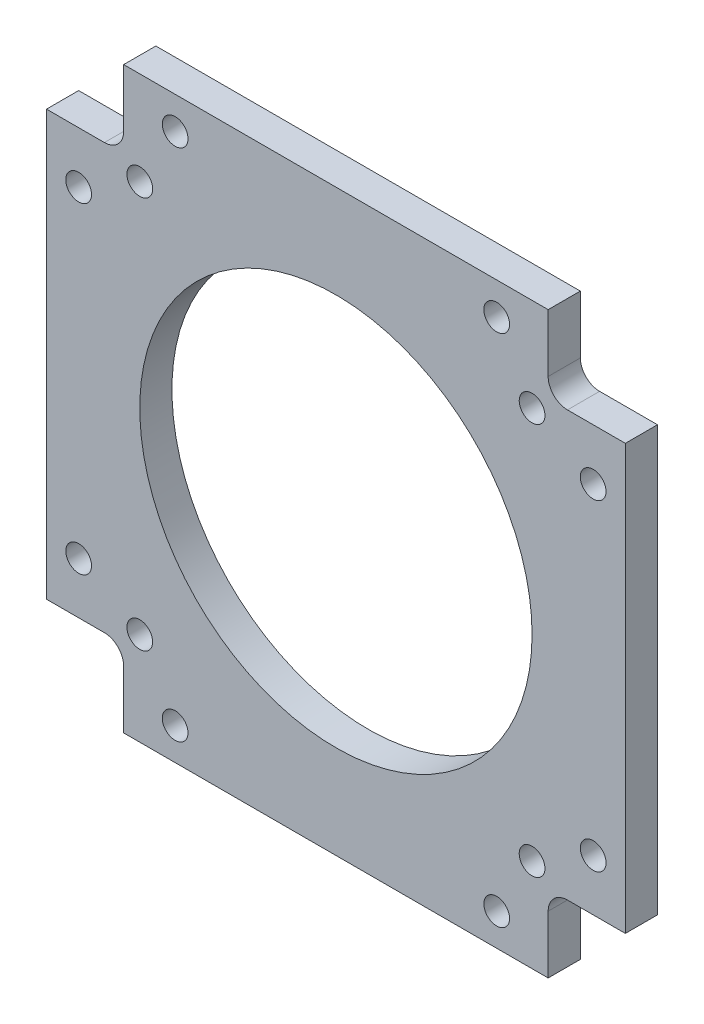
SolidWorks part; units mm, degrees
ref_plane "Front Plane" through (0, 0, 0) normal (0, 0, 1) x (1, 0, 0)
ref_plane "Top Plane" through (0, 0, 0) normal (0, 1, 0) x (1, 0, 0)
ref_plane "Right Plane" through (0, 0, 0) normal (1, 0, 0) x (0, 0, -1)
sketch "Sketch1" plane through (0, 0, 0) normal (0, 0, 1) x (1, 0, 0)
  line L0 (0, 45) -> (0, 0) construction
  line L1 (33, -45) -> (-33, -45)
  line L2 (45, -33) -> (45, 33)
  line L3 (33, 45) -> (-33, 45)
  line L4 (-45, -33) -> (-45, 33)
  line L5 (33, -33) -> (-33, 33) construction
  line L6 (33, 33) -> (-33, -33) construction
  line L7 (30.5, -30.5) -> (-30.5, -30.5) construction
  line L8 (30.5, -30.5) -> (30.5, 30.5) construction
  line L9 (30.5, 30.5) -> (-30.5, 30.5) construction
  line L10 (-30.5, -30.5) -> (-30.5, 30.5) construction
  line L11 (30.5, -30.5) -> (-30.5, 30.5) construction
  line L12 (30.5, 30.5) -> (-30.5, -30.5) construction
  line L13 (0, 0) -> (45, 0) construction
  line L14 (-33, 45) -> (-33, 33)
  line L15 (-33, 33) -> (-45, 33)
  line L16 (33, 33) -> (45, 33)
  line L17 (33, 45) -> (33, 33)
  line L18 (33, -33) -> (45, -33)
  line L19 (33, -45) -> (33, -33)
  line L20 (-33, -33) -> (-45, -33)
  line L21 (-33, -45) -> (-33, -33)
  circle A0 centre (0, 0) radius 30.5
  circle A1 centre (-30.5, 30.5) radius 2
  circle A2 centre (30.5, 30.5) radius 2
  circle A3 centre (30.5, -30.5) radius 2
  circle A4 centre (-30.5, -30.5) radius 2
  point P0 (0, 0)
  dimension "D1" = 61
  dimension "D4" = 4
  dimension "D2" = 61
  dimension "D3" = 61
  dimension "D5" = 90
  dimension "D6" = 90
  dimension "D7" = 12
  dimension "D8" = 12
extrude "Boss-Extrude1" add sketch "Sketch1" along normal blind 5
fillet "Fillet1" radius 3 4 edges at (33, -33, 2.5) (-33, -33, 2.5) (-33, 33, 2.5) (33, 33, 2.5)
sketch "Sketch2" plane through (0, 0, 0) normal (0, 0, -1) x (-1, 0, 0)
  line L0 (0, 45) -> (0, 0) construction
  line L1 (-33, 45) -> (33, 45) construction
  line L2 (0, 0) -> (45, 0) construction
  line L3 (45, 33) -> (45, -33) construction
  line L4 (-30.9779, 40) -> (31.7722, 40) construction
  line L5 (40, 28.2971) -> (40, -18.964) construction
  circle A0 centre (-25, 40) radius 2
  circle A1 centre (40, 25) radius 2
  circle A2 centre (25, 40) radius 2
  circle A3 centre (25, -40) radius 2
  circle A4 centre (-25, -40) radius 2
  circle A5 centre (40, -25) radius 2
  circle A6 centre (-40, 25) radius 2
  circle A7 centre (-40, -25) radius 2
  dimension "D2" = 5
  dimension "D3" = 50
  dimension "D4" = 50
  dimension "D5" = 4
  dimension "D6" = 4
  dimension "D1" = 5
extrude "Cut-Extrude1" cut sketch "Sketch2" against normal up to next
